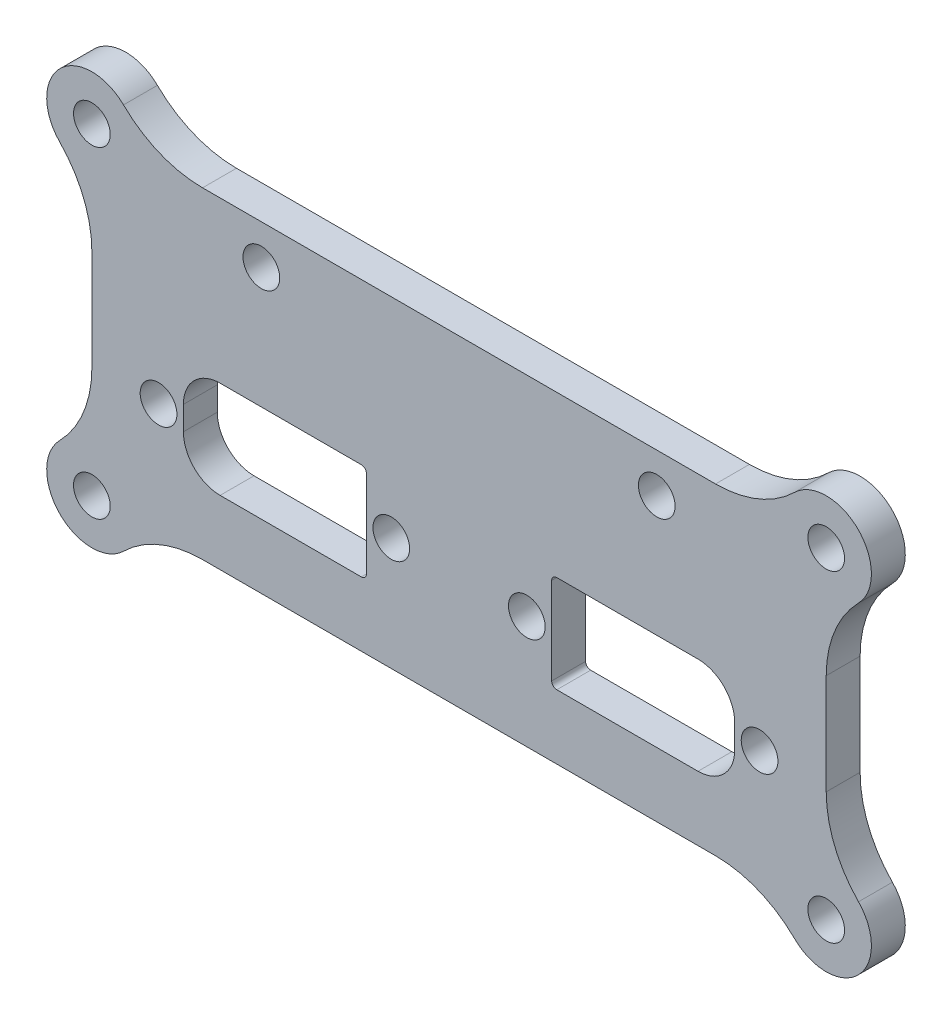
SolidWorks part; units mm, degrees
material "ABS"
ref_plane "Спереди" through (0, 0, 0) normal (0, 0, 1) x (1, 0, 0)
ref_plane "Сверху" through (0, 0, 0) normal (0, 1, 0) x (1, 0, 0)
ref_plane "Справа" through (0, 0, 0) normal (1, 0, 0) x (0, 0, -1)
sketch "Эскиз1" plane through (0, 0, 0) normal (0, 0, 1) x (1, 0, 0)
  line L0 (-32.5, 0) -> (32.5, 0)
  line L3 (-32.5, 28.5) -> (32.5, 28.5)
  line L4 (32.5, 0) -> (32.5, 28.5)
  line L6 (-32.5, 28.5) -> (0, 0) construction
  line L7 (-32.5, 0) -> (-32.5, 28.5)
  line L8 (0, 0) -> (32.5, 28.5) construction
  circle A0 centre (-32.5, 28.5) radius 1.625
  arc A1 (-28.5, 28.5) -> (-32.5, 24.5) centre (-32.5, 28.5) ccw
  circle A2 centre (32.5, 28.5) radius 1.625
  arc A3 (32.5, 24.5) -> (28.5, 28.5) centre (32.5, 28.5) ccw
  arc A8 (-30.2165, -39.7842) -> (-30.0697, -39.6771) centre (-32.5, -36.5) ccw [skipped]
  arc A9 (-30.8963, -36.7625) -> (-30.8944, -36.7501) centre (-32.5, -36.5) ccw [skipped]
  arc A10 (34.8906, -39.707) -> (34.7835, -39.7842) centre (32.5, -36.5) ccw [skipped]
  arc A11 (34.1056, -36.7501) -> (34.1094, -36.7244) centre (32.5, -36.5) ccw [skipped]
  circle A12 centre (-32.5, 0) radius 1.625
  arc A13 (-32.5, 4) -> (-28.5, 0) centre (-32.5, 0) ccw
  arc A14 (28.5, 0) -> (32.5, 4) centre (32.5, 0) ccw
  circle A15 centre (32.5, 0) radius 1.625
  point P0 (0, 0)
  point P20 (0, -4)
  dimension "D2" = 3.25
  dimension "D3" = 8
  dimension "D8" = 3.25
  dimension "D9" = 8
  dimension "D10" = 3.25
  dimension "D11" = 8
  dimension "D1" = 28.5
  dimension "D5" = 65
  dimension "D6" = 32.5
  dimension "D7" = 90
  dimension "D4" = 4
extrude "Бобышка-Вытянуть1" add sketch "Эскиз1" along normal blind 3
fillet "Скругление1" radius 10 8 edges at (-28.5, 28.5, 1.5) (28.5, 28.5, 1.5) (32.5, 24.5, 1.5) (-32.5, 24.5, 1.5) (32.5, 4, 1.5) (28.5, 0, 1.5) (-28.5, 0, 1.5) (-32.5, 4, 1.5)
sketch "Эскиз3" plane through (0, 0, 0) normal (0, 0, -1) x (-1, 0, 0)
  line L0 (0, 28.5) -> (0, -32.5) construction
  line L1 (22.702, 28.5) -> (-22.702, 28.5) construction
  line L3 (-31.8936, 25) -> (26.7306, 25) construction
  circle A0 centre (-17.5, 25) radius 1.625
  circle A1 centre (17.5, 25) radius 1.625
  dimension "D1" = 3.25
  dimension "D2" = 17.5
  dimension "D3" = 25
extrude "Вырез-Вытянуть1" cut sketch "Эскиз3" against normal blind 10
sketch "Эскиз4" plane through (0, 0, 3) normal (0, 0, 1) x (1, 0, 0)
  line L0 (-32.5, 10) -> (32.5, 10) construction
  line L1 (-32.5, 9.798) -> (-32.5, 18.702) construction
  line L2 (32.5, 9.798) -> (32.5, 18.702) construction
  line L3 (0, 28.5) -> (0, 0) construction
  line L4 (-22.702, 28.5) -> (22.702, 28.5) construction
  line L5 (-16.3, 18.1339) -> (-16.3, 8.5971) construction
  circle A0 centre (-26.6, 10) radius 1.625
  circle A1 centre (-6, 10) radius 1.625
  circle A2 centre (6, 10) radius 1.625
  circle A3 centre (26.6, 10) radius 1.625
  dimension "D4" = 3.25
  dimension "D1" = 20.6
  dimension "D2" = 6
  dimension "D3" = 10
extrude "Вырез-Вытянуть2" cut sketch "Эскиз4" against normal blind 10
sketch "Эскиз6" plane through (0, 0, 3) normal (0, 0, 1) x (1, 0, 0)
  line L0 (-21.15, 14.05) -> (-8.65, 14.05)
  line L1 (-8.45, 13.85) -> (-8.45, 6.15)
  line L2 (-21.15, 5.95) -> (-8.65, 5.95)
  line L3 (-24.15, 11.05) -> (-24.15, 8.95)
  line L4 (-24.15, 10) -> (-8.45, 10) construction
  line L6 (0, 28.5) -> (0, 0) construction
  line L11 (-22.702, 28.5) -> (22.702, 28.5) construction
  line L12 (-21.15, 14.3) -> (-8.65, 14.3)
  line L13 (-8.2, 13.85) -> (-8.2, 6.15)
  line L14 (-21.15, 5.7) -> (-8.65, 5.7)
  line L15 (-24.4, 11.05) -> (-24.4, 8.95)
  arc A1 (-8.45, 13.85) -> (-8.65, 14.05) centre (-8.65, 13.85) ccw
  arc A2 (-8.65, 5.95) -> (-8.45, 6.15) centre (-8.65, 6.15) ccw
  arc A3 (-21.15, 14.05) -> (-24.15, 11.05) centre (-21.15, 11.05) ccw
  arc A4 (-21.15, 5.95) -> (-24.15, 8.95) centre (-21.15, 8.95) cw
  arc A9 (-8.2, 13.85) -> (-8.65, 14.3) centre (-8.65, 13.85) ccw
  arc A10 (-8.65, 5.7) -> (-8.2, 6.15) centre (-8.65, 6.15) ccw
  arc A11 (-21.15, 5.7) -> (-24.4, 8.95) centre (-21.15, 8.95) cw
  arc A12 (-21.15, 14.3) -> (-24.4, 11.05) centre (-21.15, 11.05) ccw
  dimension "D1" = 0.25
extrude "Вырез-Вытянуть3" cut sketch "Эскиз6" against normal blind 10
mirror "Зеркальное отражение1" about plane through (0, 0, 0) normal (1, 0, 0) of "Вырез-Вытянуть3"
